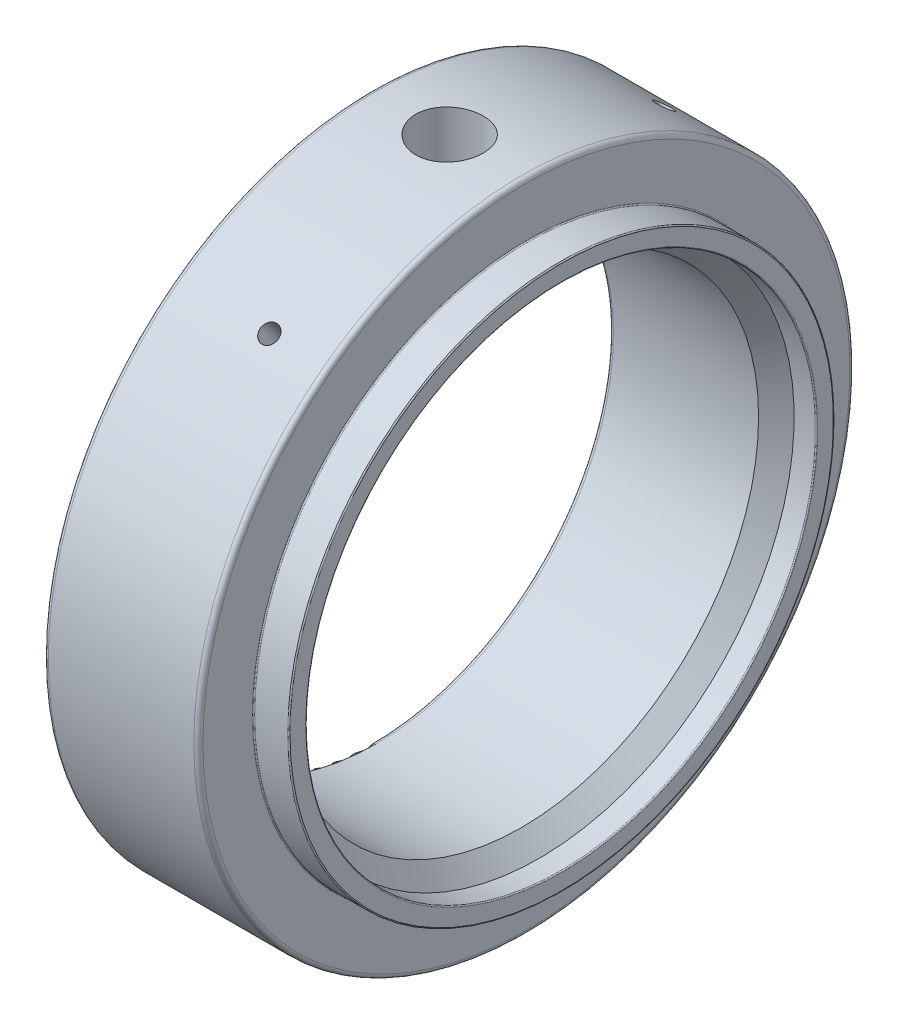
SolidWorks part; units mm, degrees
ref_plane "Front Plane" through (0, 0, 0) normal (0, 0, 1) x (1, 0, 0)
ref_plane "Top Plane" through (0, 0, 0) normal (0, 1, 0) x (1, 0, 0)
ref_plane "Right Plane" through (0, 0, 0) normal (1, 0, 0) x (0, 0, -1)
sketch "Sketch1" plane through (0, 0, 0) normal (0, 0, 1) x (1, 0, 0)
  line L0 (0, 0) -> (20.84, 0) construction
  line L2 (18.38, 27.97) -> (16.43, 26.02)
  line L3 (0.5, 36) -> (16.47, 36)
  line L4 (17.095, 29.945) -> (20.715, 29.945)
  line L5 (16.97, 35.5) -> (16.97, 30.07)
  line L6 (0, 35.5) -> (0, 26.52)
  line L7 (20.84, 29.82) -> (20.84, 28.095)
  line L8 (20.715, 27.97) -> (18.38, 27.97)
  line L9 (0.5, 26.02) -> (16.43, 26.02)
  arc A0 (0.5, 26.02) -> (0, 26.52) centre (0.5, 26.52) cw
  arc A1 (16.47, 36) -> (16.97, 35.5) centre (16.47, 35.5) cw
  arc A2 (0, 35.5) -> (0.5, 36) centre (0.5, 35.5) cw
  arc A3 (16.97, 30.07) -> (17.095, 29.945) centre (17.095, 30.07) ccw
  arc A4 (20.715, 27.97) -> (20.84, 28.095) centre (20.715, 28.095) ccw
  arc A5 (20.715, 29.945) -> (20.84, 29.82) centre (20.715, 29.82) cw
  dimension "D1" = 0.5
  dimension "D2" = 0.125
revolve "Revolve1" add sketch "Sketch1" angle 360 about L0
ref_plane "Plane1" through (0, 36, 0) normal (0, 1, 0) x (1, 0, 0)
sketch "Sketch4" plane through (0, 36, 0) normal (0, 1, 0) x (1, 0, 0)
  line L0 (0, 0) -> (17.095, 0) construction
  line L1 (17.095, -29.945) -> (17.095, 29.945) construction
  circle A0 centre (8.5475, 0) radius 3.7
extrude "Cut-Extrude2" cut sketch "Sketch4" against normal blind 6.82
ref_plane "Plane2" through (0, 28.7509, 21.6653) normal (0, 0.7986, 0.6018) x (-1, 0, 0)
sketch "Sketch6" plane through (0, 28.7509, 21.6653) normal (0, 0.7986, 0.6018) x (-1, 0, 0)
  circle A0 centre (-10.42, 0) radius 1
extrude "Cut-Extrude3" cut sketch "Sketch6" against normal blind 16.82
ref_plane "Plane3" through (0, 28.7509, -21.6653) normal (0, 0.7986, -0.6018) x (-1, 0, 0)
sketch "Sketch7" plane through (0, 28.7509, -21.6653) normal (0, 0.7986, -0.6018) x (-1, 0, 0)
  line L0 (0, 0) -> (-20.84, 0) construction
  line L1 (-20.84, 29.82) -> (-20.84, -29.82) construction
  line L2 (-20.84, 0) -> (0, 0) construction
  circle A0 centre (-10.42, 0) radius 1
extrude "Cut-Extrude4" cut sketch "Sketch7" against normal blind 16.82
